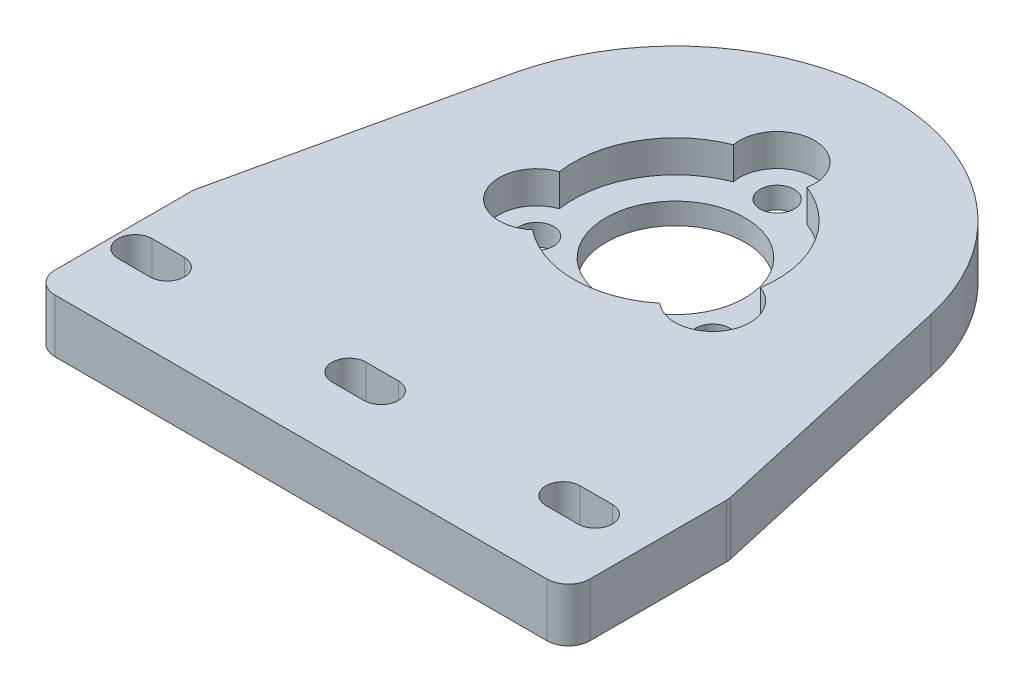
SolidWorks part; units mm, degrees
material "Thornel Mat VMA"
ref_plane "前视基准面" through (0, 0, 0) normal (0, 0, 1) x (1, 0, 0)
ref_plane "上视基准面" through (0, 0, 0) normal (0, 1, 0) x (1, 0, 0)
ref_plane "右视基准面" through (0, 0, 0) normal (1, 0, 0) x (0, 0, -1)
other "Configuration Table"
sketch "草图1" plane through (0, 0, 0) normal (0, 1, 0) x (1, 0, 0)
  circle A0 centre (0, 0) radius 6.5
  circle A1 centre (0, 0) radius 20
  circle A2 centre (0, 0) radius 9.5 construction
  circle A3 centre (0, 9.5) radius 1.6
  circle A4 centre (8.2272, -4.75) radius 1.6
  circle A5 centre (-8.2272, -4.75) radius 1.6
  point P14 (0, 0)
  dimension "D1" = 13
  dimension "30" = 40
  dimension "D3" = 19
  dimension "D4" = 3.2
  dimension "D5" = 3
extrude "凸台-拉伸1" add sketch "草图1" along normal blind 5
sketch "草图2" plane through (0, 5, 0) normal (0, 1, 0) x (1, 0, 0)
  line L0 (0, 0) -> (0, -20) construction
  line L1 (-25, -27.5) -> (25, -27.5) construction
  line L2 (-25, -20) -> (25, -20)
  line L3 (-25, -20) -> (-25, -35)
  line L4 (-25, -35) -> (25, -35)
  line L5 (25, -20) -> (25, -35)
  circle A0 centre (-20, -27.5) radius 1.6
  circle A1 centre (20, -27.5) radius 1.6
  circle A2 centre (0, -27.5) radius 1.6
  dimension "D4" = 3.2
  dimension "D5" = 3.2
  dimension "D6" = 3.2
  dimension "D1" = 20
  dimension "D2" = 50
  dimension "D3" = 15
  dimension "D7" = 5
  dimension "D8" = 5
extrude "凸台-拉伸2" add sketch "草图2" against normal blind 5 separate body
sketch "草图4" plane through (0, 5, 0) normal (0, 1, 0) x (1, 0, 0)
  line L0 (-25, -20) -> (-19.5122, 4.3902)
  line L1 (-25, -20) -> (25, -20)
  line L2 (25, -20) -> (19.5122, 4.3902)
  circle A0 centre (0, 0) radius 20 construction
  circle A1 centre (0, 0) radius 20
  line M8 (25, -20) -> (-25, -20)
extrude "凸台-拉伸4" add sketch "草图4" against normal blind 5 contours A1 L0 L1 | A1 L2 M8
sketch "草图5" plane through (0, 5, 0) normal (0, 1, 0) x (1, 0, 0)
  circle A0 centre (-8.2272, -4.75) radius 3.5
  circle A1 centre (8.2272, -4.75) radius 3.5
  circle A2 centre (0, 9.5) radius 3.5
  circle A3 centre (0, 0) radius 9.5
  circle M1 centre (8.2272, -4.75) radius 1.6
  circle M2 centre (0, 0) radius 6.5
  circle M9 centre (0, 9.5) radius 1.6
  circle M10 centre (-8.2272, -4.75) radius 1.6
  dimension "D1" = 7
  dimension "D2" = 7
  dimension "D3" = 7
extrude "切除-拉伸1" cut sketch "草图5" against normal blind 3 contours A3 A0 M10 | A0 A3 M10 M2 | A0 M2 | A2 A3 A0 M2 | A2 A3 M9 M2 | A3 A2 M9 | A3 A1 M1 | A1 A3 M1 M2 | A1 A3 A2 M2 | A0 A3 A1 M2 | A1 M2
fillet "圆角1" radius 2 4 edges at (-25, 2.5, 20) (-25, 2.5, 35) (25, 2.5, 20) (25, 2.5, 35)
sketch "草图6" plane through (0, 0, 0) normal (0, -1, 0) x (1, 0, 0)
  line L0 (20, 27.5) -> (17, 27.5) construction
  line L2 (20, 25.9) -> (17, 25.9)
  line L3 (20, 29.1) -> (17, 29.1)
  line L4 (0, 27.5) -> (-3, 27.5) construction
  line L5 (0, 25.9) -> (-3, 25.9)
  line L6 (0, 29.1) -> (-3, 29.1)
  line L7 (-20, 27.5) -> (-23, 27.5) construction
  line L8 (-20, 25.9) -> (-23, 25.9)
  line L9 (-20, 29.1) -> (-23, 29.1)
  arc A0 (20, 25.9) -> (20, 29.1) centre (20, 27.5) ccw
  arc A1 (17, 29.1) -> (17, 25.9) centre (17, 27.5) ccw
  arc A2 (0, 25.9) -> (0, 29.1) centre (0, 27.5) ccw
  arc A3 (-3, 29.1) -> (-3, 25.9) centre (-3, 27.5) ccw
  arc A4 (-20, 25.9) -> (-20, 29.1) centre (-20, 27.5) ccw
  arc A5 (-23, 29.1) -> (-23, 25.9) centre (-23, 27.5) ccw
  point P5 (18.5, 27.5)
  point P10 (-1.5, 27.5)
  point P18 (-21.5, 27.5)
extrude "切除-拉伸2" cut sketch "草图6" against normal through all
